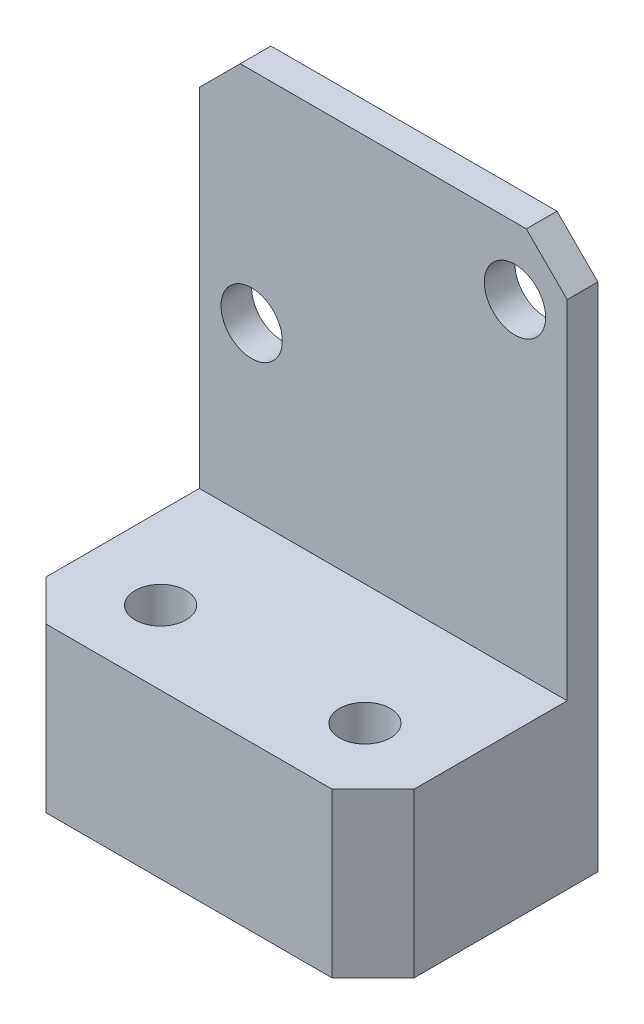
SolidWorks part; units mm, degrees
ref_plane "Front" through (0, 0, 0) normal (0, 0, 1) x (1, 0, 0)
ref_plane "Top" through (0, 0, 0) normal (0, 1, 0) x (1, 0, 0)
ref_plane "Right" through (0, 0, 0) normal (1, 0, 0) x (0, 0, -1)
sketch "Sketch1" plane through (0, 0, 0) normal (0, 0, 1) x (1, 0, 0)
  line L1 (-9, 7) -> (9, 7)
  line L2 (-9, 7) -> (-9, -20)
  line L3 (-9, -20) -> (9, -20)
  line L4 (9, 7) -> (9, -20)
  dimension "D1" = 9
  dimension "D2" = 9
  dimension "D3" = 7
  dimension "D4" = 20
extrude "Extrude1" add sketch "Sketch1" along normal blind 11
sketch "Sketch2" plane through (0, 0, 11) normal (0, 0, 1) x (1, 0, 0)
  line L0 (9, -20) -> (9, 7) construction
  line L1 (-9, 7) -> (9, 7)
  line L2 (-9, 7) -> (-9, -12)
  line L3 (-9, -12) -> (9, -12)
  line L4 (9, 7) -> (9, -12)
  line L5 (-9, -20) -> (9, -20) construction
  dimension "D1" = 8
extrude "Extrude2" cut sketch "Sketch2" against normal blind 9.5
sketch "Sketch3" plane through (0, 0, 1.5) normal (0, 0, 1) x (1, 0, 0)
  circle A0 centre (6.4432, 3.72) radius 1.5
  circle A1 centre (-6.4432, -3.72) radius 1.5
  dimension "D5" = 3
  dimension "D6" = 3
  dimension "D1" = 7.44
  dimension "D2" = 7.44
  dimension "D3" = 3.72
  dimension "D4" = 3.72
extrude "Extrude3" cut sketch "Sketch3" against normal up to surface (1.5 mm away) up to face at (0, -6.5, 0)
sketch "Sketch4" plane through (0, -12, 0) normal (0, 1, 0) x (1, 0, 0)
  line L1 (-9, -1.5) -> (-9, -11) construction
  line L2 (9, -1.5) -> (9, -11) construction
  line L3 (-9, -1.5) -> (9, -1.5) construction
  circle A0 centre (-5, -7.4) radius 1.25
  circle A1 centre (5, -7.4) radius 1.25
  dimension "D3" = 2.5
  dimension "D4" = 2.5
  dimension "D1" = 5.9
  dimension "D2" = 5.9
  dimension "D5" = 4
  dimension "D6" = 4
extrude "Extrude4" cut sketch "Sketch4" against normal up to surface (8 mm away) up to face at (0, -20, 5.5)
cosmetic thread "Hole Thread1" parameters "D1"=8, "D2"=3
cosmetic thread "Hole Thread2" parameters "D1"=8, "D2"=3
hole_wizard "M3 Tapped Hole1" positions "3DSketch1" profile "Sketch5" tap size "M3" standard "DIN"
sketch3d "3DSketch1"
  line L0 (5, -20, 7.4) -> (5, -12, 7.4) construction
  line L1 (-5, -20, 7.4) -> (-5, -12, 7.4) construction
  point P0 (5, -20, 7.4)
  point P4 (-5, -20, 7.4)
sketch "Sketch5" plane through (5, -20, 7.4) normal (1, 0, 0) x (0, 0, -1)
  line L0 (0, 0) -> (0, 12.2511)
  line L1 (0, 12.2511) -> (1.25, 11.5)
  line L2 (1.25, 11.5) -> (1.25, 0)
  line L5 (1.25, 0) -> (0, 0)
  line L10 (0, 12.2511) -> (-1.25, 11.5) construction
  line L11 (0, -6.35) -> (0, 107.95) construction
  dimension "Tap Drill Dia." = 2.5
  dimension "Tap Drill Depth" = 11.5
  dimension "Drill Angle" = 118
chamfer "Chamfer1" distance 2 angle 45 4 edges at (-9, 7, 0.75) (9, 7, 0.75) (-9, -16, 11) (9, -16, 11)
